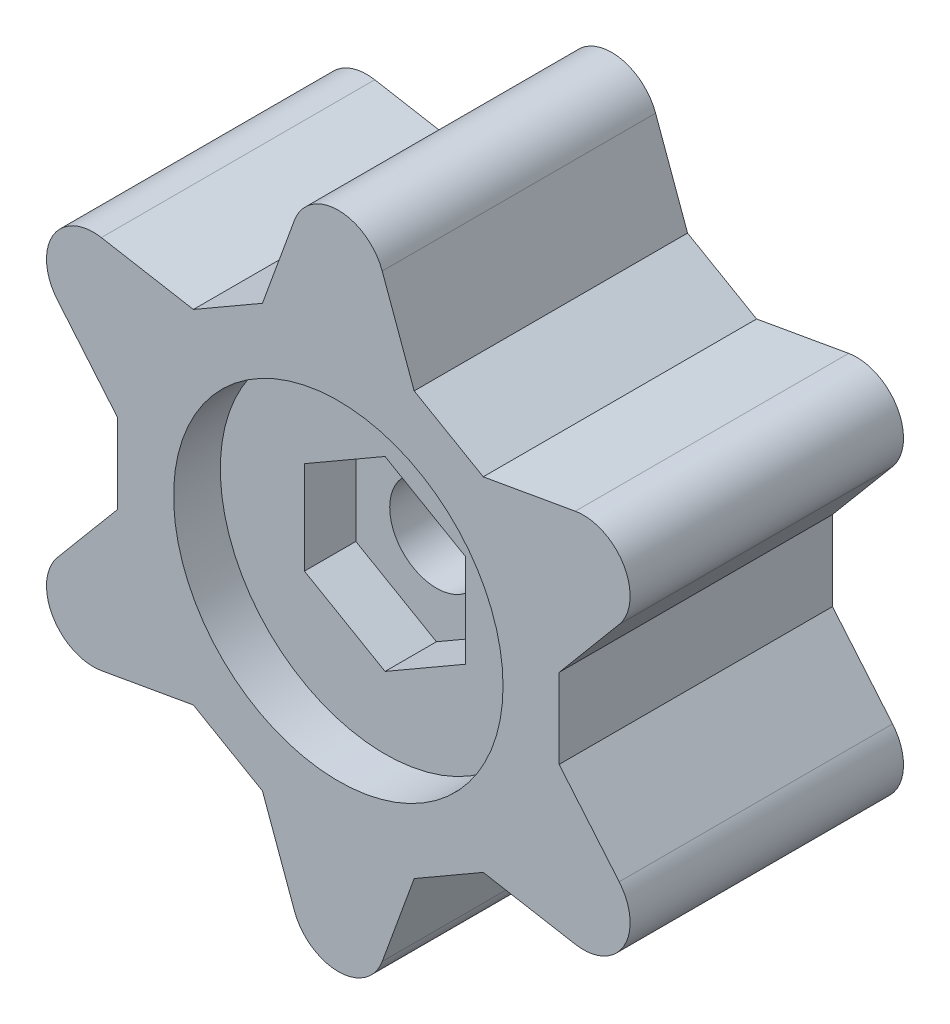
SolidWorks part; units mm, degrees
ref_plane "Front Plane" through (0, 0, 0) normal (0, 0, 1) x (1, 0, 0)
ref_plane "Top Plane" through (0, 0, 0) normal (0, 1, 0) x (1, 0, 0)
ref_plane "Right Plane" through (0, 0, 0) normal (1, 0, 0) x (0, 0, -1)
sketch "Sketch1" plane through (0, 0, 0) normal (0, 0, 1) x (1, 0, 0)
  line L0 (-3.2475, 9.037) -> (-1.8794, 12.7958)
  line L1 (3.45, -1.9919) -> (3.45, 1.9919)
  line L2 (3.45, 1.9919) -> (0, 3.9837)
  line L3 (0, 3.9837) -> (-3.45, 1.9919)
  line L4 (-3.45, 1.9919) -> (-3.45, -1.9919)
  line L5 (-3.45, -1.9919) -> (0, -3.9837)
  line L6 (0, -3.9837) -> (3.45, -1.9919)
  line L7 (1.8794, 12.7958) -> (3.2475, 9.037)
  line L8 (6.2025, 7.3309) -> (10.1418, 8.0255)
  line L9 (12.0212, 4.7703) -> (9.45, 1.7061)
  line L10 (9.45, -1.7061) -> (12.0212, -4.7703)
  line L11 (10.1418, -8.0255) -> (6.2025, -7.3309)
  line L12 (3.2475, -9.037) -> (1.8794, -12.7958)
  line L13 (-1.8794, -12.7958) -> (-3.2475, -9.037)
  line L14 (-6.2025, -7.3309) -> (-10.1418, -8.0255)
  line L15 (-12.0212, -4.7703) -> (-9.45, -1.7061)
  line L16 (-9.45, 1.7061) -> (-12.0212, 4.7703)
  line L17 (-10.1418, 8.0255) -> (-6.2025, 7.3309)
  line L18 (-6.2025, 7.3309) -> (-3.2475, 9.037)
  line L19 (3.2475, 9.037) -> (6.2025, 7.3309)
  line L20 (9.45, 1.7061) -> (9.45, -1.7061)
  line L21 (6.2025, -7.3309) -> (3.2475, -9.037)
  line L22 (-3.2475, -9.037) -> (-6.2025, -7.3309)
  line L23 (-9.45, -1.7061) -> (-9.45, 1.7061)
  circle A0 centre (0, 0) radius 3.45 construction
  arc A2 (-1.8794, 12.7958) -> (1.8794, 12.7958) centre (0, 12.1117) cw
  arc A3 (10.1418, 8.0255) -> (12.0212, 4.7703) centre (10.4891, 6.0559) cw
  arc A4 (12.0212, -4.7703) -> (10.1418, -8.0255) centre (10.4891, -6.0559) cw
  arc A5 (1.8794, -12.7958) -> (-1.8794, -12.7958) centre (0, -12.1117) cw
  arc A6 (-10.1418, -8.0255) -> (-12.0212, -4.7703) centre (-10.4891, -6.0559) cw
  arc A7 (-12.0212, 4.7703) -> (-10.1418, 8.0255) centre (-10.4891, 6.0559) cw
  point P13 (-6.333, -1.2944)
  point P16 (-5.7428, 2.5753)
  point P41 (-9.45, 0)
  point P42 (-3.45, 0)
  point P43 (9.45, 0)
  point P44 (3.45, 0)
  point P45 (-3.45, -3.6678)
  point P46 (7.1532, 4.1299)
  point P47 (6.9415, 3.9837)
  dimension "D1" = 6.9
  dimension "D2" = 2
  dimension "D3" = 6
  dimension "D5" = 40
  dimension "D6" = 4
  dimension "D4" = 6
extrude "Boss-Extrude1" add sketch "Sketch1" along normal blind 9.7
sketch "Sketch5" plane through (0, 0, 0) normal (0, 0, -1) x (-1, 0, 0)
  line L0 (-3.45, 1.9919) -> (0, 3.9837) construction
  line L1 (-3.45, -1.9919) -> (-3.45, 1.9919) construction
  line L2 (0, -3.9837) -> (-3.45, -1.9919) construction
  line L3 (3.45, -1.9919) -> (0, -3.9837) construction
  line L4 (3.45, 1.9919) -> (3.45, -1.9919) construction
  line L5 (0, 3.9837) -> (3.45, 1.9919) construction
  line L6 (-3.45, 1.9919) -> (0, 3.9837)
  line L7 (-3.45, -1.9919) -> (-3.45, 1.9919)
  line L8 (0, -3.9837) -> (-3.45, -1.9919)
  line L9 (3.45, -1.9919) -> (0, -3.9837)
  line L10 (3.45, 1.9919) -> (3.45, -1.9919)
  line L11 (0, 3.9837) -> (3.45, 1.9919)
  circle A0 centre (0, 0) radius 2
  dimension "D1" = 4
extrude "Boss-Extrude2" add sketch "Sketch5" against normal blind 7.5
sketch "Sketch6" plane through (0, 0, 9.7) normal (0, 0, 1) x (1, 0, 0)
  line L18 (-3.2475, 9.037) -> (-6.2025, 7.3309)
  line L19 (-6.2025, 7.3309) -> (-10.1418, 8.0255)
  line L20 (-12.0212, 4.7703) -> (-9.45, 1.7061)
  line L21 (-9.45, 1.7061) -> (-9.45, -1.7061)
  line L22 (-9.45, -1.7061) -> (-12.0212, -4.7703)
  line L23 (-10.1418, -8.0255) -> (-6.2025, -7.3309)
  line L24 (-6.2025, -7.3309) -> (-3.2475, -9.037)
  line L25 (-3.2475, -9.037) -> (-1.8794, -12.7958)
  line L26 (1.8794, -12.7958) -> (3.2475, -9.037)
  line L27 (3.2475, -9.037) -> (6.2025, -7.3309)
  line L28 (6.2025, -7.3309) -> (10.1418, -8.0255)
  line L29 (12.0212, -4.7703) -> (9.45, -1.7061)
  line L30 (9.45, -1.7061) -> (9.45, 1.7061)
  line L31 (9.45, 1.7061) -> (12.0212, 4.7703)
  line L32 (10.1418, 8.0255) -> (6.2025, 7.3309)
  line L33 (6.2025, 7.3309) -> (3.2475, 9.037)
  line L34 (3.2475, 9.037) -> (1.8794, 12.7958)
  line L35 (-1.8794, 12.7958) -> (-3.2475, 9.037)
  line L36 (-3.2475, 9.037) -> (-6.2025, 7.3309)
  line L37 (-6.2025, 7.3309) -> (-10.1418, 8.0255)
  line L38 (-12.0212, 4.7703) -> (-9.45, 1.7061)
  line L39 (-9.45, 1.7061) -> (-9.45, -1.7061)
  line L40 (-9.45, -1.7061) -> (-12.0212, -4.7703)
  line L41 (-10.1418, -8.0255) -> (-6.2025, -7.3309)
  line L42 (-6.2025, -7.3309) -> (-3.2475, -9.037)
  line L43 (-3.2475, -9.037) -> (-1.8794, -12.7958)
  line L44 (1.8794, -12.7958) -> (3.2475, -9.037)
  line L45 (3.2475, -9.037) -> (6.2025, -7.3309)
  line L46 (6.2025, -7.3309) -> (10.1418, -8.0255)
  line L47 (12.0212, -4.7703) -> (9.45, -1.7061)
  line L48 (9.45, -1.7061) -> (9.45, 1.7061)
  line L49 (9.45, 1.7061) -> (12.0212, 4.7703)
  line L50 (10.1418, 8.0255) -> (6.2025, 7.3309)
  line L51 (6.2025, 7.3309) -> (3.2475, 9.037)
  line L52 (3.2475, 9.037) -> (1.8794, 12.7958)
  line L53 (-1.8794, 12.7958) -> (-3.2475, 9.037)
  circle A0 centre (0, 0) radius 7.05
  arc A6 (-10.1418, 8.0255) -> (-12.0212, 4.7703) centre (-10.4891, 6.0559) ccw
  arc A7 (-12.0212, -4.7703) -> (-10.1418, -8.0255) centre (-10.4891, -6.0559) ccw
  arc A8 (-1.8794, -12.7958) -> (1.8794, -12.7958) centre (0, -12.1117) ccw
  arc A9 (10.1418, -8.0255) -> (12.0212, -4.7703) centre (10.4891, -6.0559) ccw
  arc A10 (12.0212, 4.7703) -> (10.1418, 8.0255) centre (10.4891, 6.0559) ccw
  arc A11 (1.8794, 12.7958) -> (-1.8794, 12.7958) centre (0, 12.1117) ccw
  arc A12 (-10.1418, 8.0255) -> (-12.0212, 4.7703) centre (-10.4891, 6.0559) ccw
  arc A13 (-12.0212, -4.7703) -> (-10.1418, -8.0255) centre (-10.4891, -6.0559) ccw
  arc A14 (-1.8794, -12.7958) -> (1.8794, -12.7958) centre (0, -12.1117) ccw
  arc A15 (10.1418, -8.0255) -> (12.0212, -4.7703) centre (10.4891, -6.0559) ccw
  arc A16 (12.0212, 4.7703) -> (10.1418, 8.0255) centre (10.4891, 6.0559) ccw
  arc A17 (1.8794, 12.7958) -> (-1.8794, 12.7958) centre (0, 12.1117) ccw
  dimension "D2" = 14.1
  dimension "D1" = 0
extrude "Boss-Extrude3" add sketch "Sketch6" along normal blind 2
